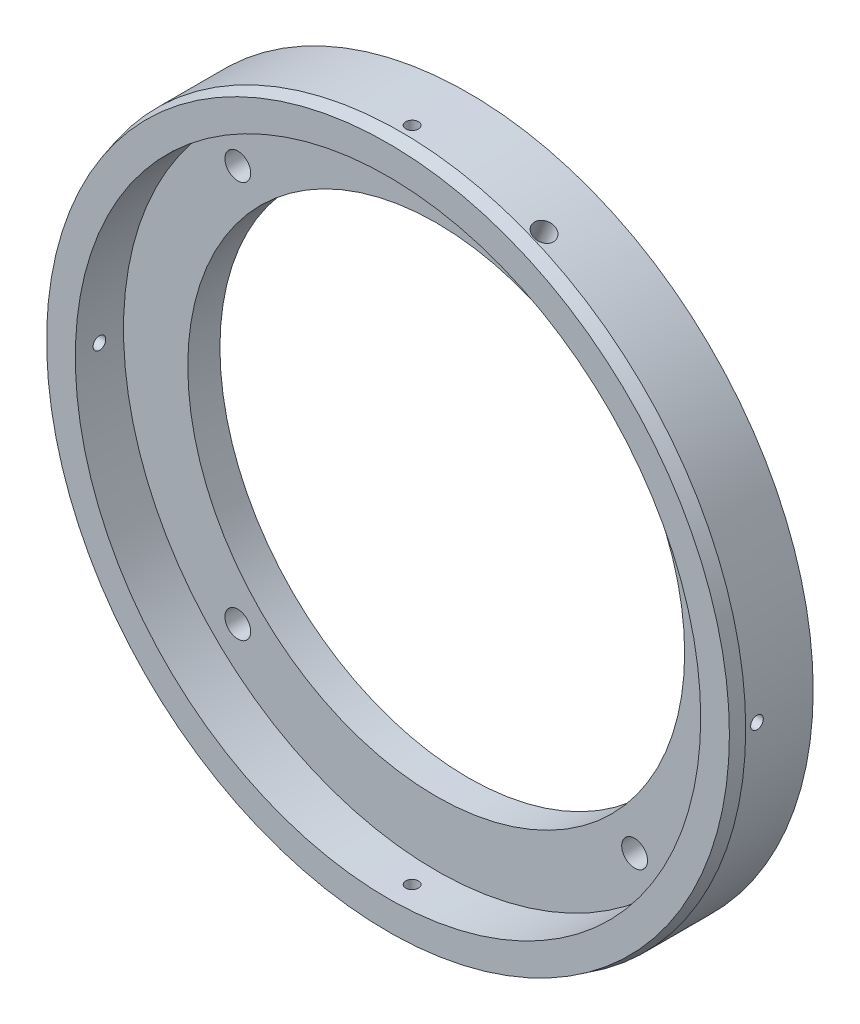
SolidWorks part; units mm, degrees
material "6061-T6 (SS)"
ref_plane "Front Plane" through (0, 0, 0) normal (0, 0, 1) x (1, 0, 0)
ref_plane "Top Plane" through (0, 0, 0) normal (0, 1, 0) x (1, 0, 0)
ref_plane "Right Plane" through (0, 0, 0) normal (1, 0, 0) x (0, 0, -1)
sketch "Sketch1" plane through (0, 0, 0) normal (0, 0, 1) x (1, 0, 0)
  circle A0 centre (0, 0) radius 68.1355
  circle A1 centre (0, 0) radius 49.0855
  dimension "D1" = 136.271
  dimension "D2" = 98.171
extrude "Extrude1" add sketch "Sketch1" along normal blind 15.875
sketch "Sketch2" plane through (0, 0, 15.875) normal (0, 0, 1) x (1, 0, 0)
  circle A0 centre (0, 0) radius 61.7855
extrude "Extrude2" cut sketch "Sketch2" against normal blind 9.525
ref_plane "Plane1" through (0, 0, 11.1125) normal (0, 0, 1) x (1, 0, 0)
sketch "Sketch3" plane through (0, 0, 11.1125) normal (0, 0, 1) x (1, 0, 0)
  line L0 (0, 0) -> (0, 68.1355) construction
  line L1 (0, 0) -> (26.0743, 62.949) construction
  circle A0 centre (0, 0) radius 68.1355 construction
  arc A1 (0, 68.1355) -> (26.0743, 62.949) centre (0, 0) cw
  circle A2 centre (0, 0) radius 55.4355
  arc A3 (0, 55.4355) -> (39.1988, 39.1988) centre (0, 0) cw
ref_plane "Plane3" through (26.0743, 62.949, 11.1125) normal (0.3827, 0.9239, 0) x (-0.9239, 0.3827, 0)
hole_wizard "Tap Drill for #10-32 Tap1" positions "Sketch7" profile "Sketch6" hole size "#10-32" standard "Ansi Inch"
sketch "Sketch7" plane through (26.0743, 62.949, 11.1125) normal (0.3827, 0.9239, 0) x (-0.9239, 0.3827, 0)
  point P1 (0, 0)
sketch "Sketch6" plane through (26.0743, 62.949, 11.1125) normal (0, 0, 1) x (-0.9239, 0.3827, 0)
  line L0 (0, 0) -> (0, 13.9133)
  line L1 (0, 13.9133) -> (2.0193, 12.7)
  line L2 (2.0193, 12.7) -> (2.0193, 0)
  line L5 (2.0193, 0) -> (0, 0)
  line L10 (0, 13.9133) -> (-2.0193, 12.7) construction
  line L11 (0, -6.35) -> (0, 107.95) construction
  dimension "Hole Dia." = 4.0386
  dimension "Hole Depth" = 12.7
  dimension "Drill Angle" = 118
ref_plane "Plane2" through (0, 68.1355, 11.1125) normal (0, 1, 0) x (-1, 0, 0)
hole_wizard "M3x0.5 Tapped Hole1" positions "Sketch5" profile "Sketch4" tap size "M3x0.5" standard "Ansi Metric"
sketch "Sketch5" plane through (0, 68.1355, 11.1125) normal (0, 1, 0) x (-1, 0, 0)
  point P1 (0, 0)
sketch "Sketch4" plane through (0, 68.1355, 11.1125) normal (1, 0, 0) x (0, 0, 1)
  line L0 (0, 0) -> (0, 9.3871)
  line L1 (0, 9.3871) -> (1.25, 8.636)
  line L2 (1.25, 8.636) -> (1.25, 0)
  line L5 (1.25, 0) -> (0, 0)
  line L10 (0, 9.3871) -> (-1.25, 8.636) construction
  line L11 (0, -6.35) -> (0, 107.95) construction
  dimension "Tap Drill Dia." = 2.5
  dimension "Tap Drill Depth" = 8.636
  dimension "Drill Angle" = 118
cosmetic thread "Hole Thread1" parameters "D1"=6.096, "D2"=3
pattern_circular "CirPattern1" count 4 over 360 about axis through (0, 0, 15.875) along (0, 0, -1) of "M3x0.5 Tapped Hole1"
sketch "Sketch11" plane through (0, 0, 6.35) normal (0, 0, 1) x (1, 0, 0)
  arc A0 (39.1988, 39.1988) -> (46.0929, 30.7983) centre (0, 0) cw construction
  arc A1 (46.0929, 30.7983) -> (51.2157, 21.2142) centre (0, 0) cw construction
hole_wizard "1/4-20 Tapped Hole1" positions "Sketch9" profile "Sketch8" tap size "1/4-20" standard "Ansi Inch"
sketch "Sketch9" plane through (0, 0, 11.1125) normal (0, 0, 1) x (1, 0, 0)
  point P1 (39.1988, 39.1988)
sketch "Sketch8" plane through (39.1988, 39.1988, 11.1125) normal (1, 0, 0) x (0, -1, 0)
  line L0 (0, 0) -> (0, 18.0438)
  line L1 (0, 18.0438) -> (2.5527, 16.51)
  line L2 (2.5527, 16.51) -> (2.5527, 0)
  line L5 (2.5527, 0) -> (0, 0)
  line L10 (0, 18.0438) -> (-2.5527, 16.51) construction
  line L11 (0, -6.35) -> (0, 107.95) construction
  dimension "Tap Drill Dia." = 5.1054
  dimension "Tap Drill Depth" = 16.51
  dimension "Drill Angle" = 118
cosmetic thread "Hole Thread2" parameters "D1"=6.35, "D2"=6.35
pattern_circular "CirPattern2" count 4 over 360 about axis through (0, 0, 0) along (0, 0, 1) of "1/4-20 Tapped Hole1"
chamfer "Chamfer1" distance 2.54 angle 15 1 edges at (68.1355, 0, 15.875)
sketch "Sketch10" plane through (0, 0, 0) normal (0, 0, -1) x (-1, 0, 0)
  circle A0 centre (0, 0) radius 55.4355 construction
  point P0 (-39.1988, 39.1988)
  point P1 (39.1988, 39.1988)
  point P3 (39.1988, -39.1988)
  point P5 (-39.1988, -39.1988)
hole_wizard "1/4 (0.25) Diameter Hole1" [suppressed] positions "3DSketch1" profile "Sketch12" hole size "1/4" standard "Ansi Inch"
sketch3d "3DSketch1"
  point P0 (46.0929, 30.7983, 6.35)
sketch "Sketch12" plane through (46.0929, 30.7983, 6.35) normal (1, 0, 0) x (0, -1, 0)
  line L0 (0, 0) -> (0, 14.6077)
  line L1 (0, 14.6077) -> (3.175, 12.7)
  line L2 (3.175, 12.7) -> (3.175, 0)
  line L5 (3.175, 0) -> (0, 0)
  line L10 (0, 14.6077) -> (-3.175, 12.7) construction
  line L11 (0, -6.35) -> (0, 107.95) construction
  dimension "Hole Dia." = 6.35
  dimension "Hole Depth" = 12.7
  dimension "Drill Angle" = 118
hole_wizard "7/16 (0.4375) Diameter Hole1" [suppressed] positions "3DSketch2" profile "Sketch13" hole size "7/16" standard "Ansi Inch"
sketch3d "3DSketch2"
  point P0 (51.2157, 21.2142, 6.35)
sketch "Sketch13" plane through (51.2157, 21.2142, 6.35) normal (1, 0, 0) x (0, -1, 0)
  line L0 (0, 0) -> (0, 16.0385)
  line L1 (0, 16.0385) -> (5.5562, 12.7)
  line L2 (5.5562, 12.7) -> (5.5562, 0)
  line L5 (5.5562, 0) -> (0, 0)
  line L10 (0, 16.0385) -> (-5.5563, 12.7) construction
  line L11 (0, -6.35) -> (0, 107.95) construction
  dimension "Hole Dia." = 11.1125
  dimension "Hole Depth" = 12.7
  dimension "Drill Angle" = 118
sketch "Sketch15" [suppressed] plane through (0, 0, 6.35) normal (0, 0, 1) x (1, 0, 0)
  line L0 (43.453, 29.0344) -> (48.7328, 32.5622)
  line L1 (47.0709, 22.7043) -> (52.7904, 25.4631)
  arc A0 (43.453, 29.0344) -> (47.0709, 22.7043) centre (0, 0) cw
  circle A1 centre (46.0929, 30.7983) radius 3.175 construction
  arc A2 (48.7328, 32.5622) -> (52.7904, 25.4631) centre (0, 0) cw
extrude "Extrude3" [suppressed] cut sketch "Sketch15" against normal through all
pattern_circular "CirPattern3" [suppressed] count 4 over 360
sketch "Sketch16" [suppressed] plane through (0, 0, 0) normal (0, 0, -1) x (-1, 0, 0)
  point P0 (-46.0929, 30.7983)
  point P1 (30.7983, 46.0929)
  point P3 (46.0929, -30.7983)
  point P5 (-30.7983, -46.0929)
